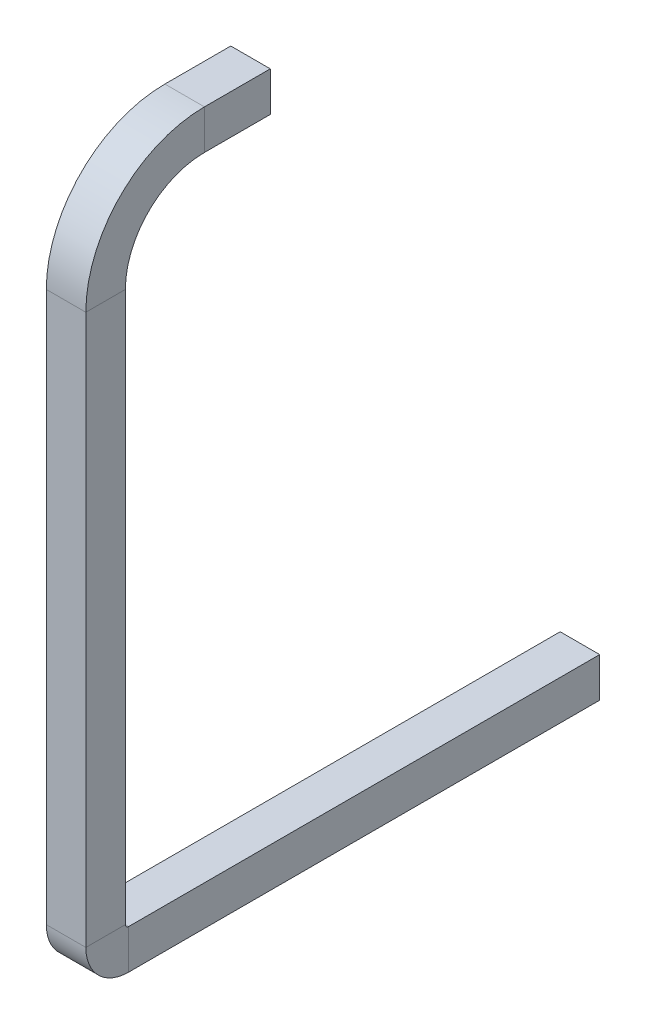
SolidWorks part; units mm, degrees
material "Brass"
ref_plane "Front" through (0, 0, 0) normal (0, 0, 1) x (1, 0, 0)
ref_plane "Top" through (0, 0, 0) normal (0, 1, 0) x (1, 0, 0)
ref_plane "Right" through (0, 0, 0) normal (1, 0, 0) x (0, 0, -1)
sketch "Sketch1" plane through (0, 0, 0) normal (1, 0, 0) x (0, 0, -1)
  line L0 (5, -10.2) -> (-2.15, -10.2)
  line L1 (-2.5, -9.85) -> (-2.5, -1.5)
  line L2 (-1, 0) -> (0, 0)
  arc A0 (-2.15, -10.2) -> (-2.5, -9.85) centre (-2.15, -9.85) cw
  arc A1 (-2.5, -1.5) -> (-1, 0) centre (-1, -1.5) cw
  dimension "D1" = 0.35
  dimension "D3" = 1.5
  dimension "D2" = 10.2
  dimension "D4" = 1
  dimension "D5" = 7.5
sketch "Sketch2" plane through (0, 0, 0) normal (0, 0, 1) x (1, 0, 0)
  line L0 (0.3, 0.3) -> (-0.3, -0.3) construction
  line L1 (0.3, 0.3) -> (-0.3, 0.3)
  line L2 (0.3, 0.3) -> (0.3, -0.3)
  line L3 (0.3, -0.3) -> (-0.3, -0.3)
  line L4 (-0.3, 0.3) -> (-0.3, -0.3)
  point P4 (0, 0)
  dimension "D1" = 0.6
sweep "Sweep1" add profiles "Sketch2" path "Sketch1"
